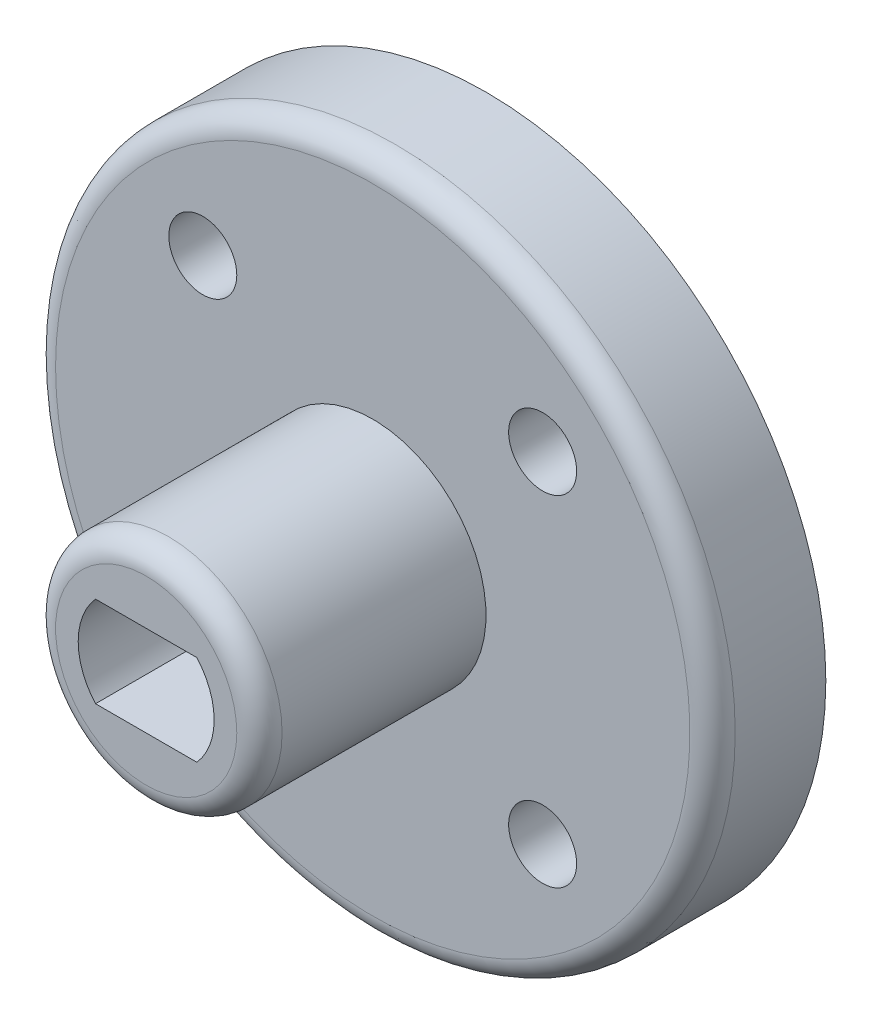
SolidWorks part; units mm, degrees
ref_plane "Alzado" through (0, 0, 0) normal (0, 0, 1) x (1, 0, 0)
ref_plane "Planta" through (0, 0, 0) normal (0, 1, 0) x (1, 0, 0)
ref_plane "Vista lateral" through (0, 0, 0) normal (1, 0, 0) x (0, 0, -1)
sketch "Croquis1" plane through (0, 0, 0) normal (0, 0, 1) x (1, 0, 0)
  line L0 (-7.3928, 0) -> (5.9139, 0) construction
  line L1 (-2.2361, -2) -> (2.2361, -2)
  line L2 (-2.2361, 2) -> (2.2361, 2)
  line L3 (-7.3928, 2) -> (5.9139, 2) construction
  line L4 (-7.3928, -2) -> (5.9139, -2) construction
  arc A0 (-2.2361, 2) -> (-2.2361, -2) centre (0, 0) ccw
  arc A1 (2.2361, -2) -> (2.2361, 2) centre (0, 0) ccw
  circle A2 centre (0, 0) radius 5
  dimension "D1" = 6
  dimension "D4" = 10
  dimension "D2" = 2
  dimension "D3" = 2
extrude "Saliente-Extruir1" add sketch "Croquis1" along normal mid plane 10
sketch "Croquis2" plane through (0, 0, -5) normal (0, 0, -1) x (-1, 0, 0)
  circle A0 centre (0, 0) radius 15
  dimension "D1" = 30
extrude "Saliente-Extruir2" add sketch "Croquis2" along normal blind 5
sketch "Croquis3" plane through (0, 0, -5) normal (0, 0, 1) x (1, 0, 0)
  line L1 (-7.5, -7.5) -> (7.5, -7.5) construction
  line L2 (-7.5, -7.5) -> (-7.5, 7.5) construction
  line L3 (-7.5, 7.5) -> (7.5, 7.5) construction
  line L4 (7.5, -7.5) -> (7.5, 7.5) construction
  line L5 (-7.5, -7.5) -> (7.5, 7.5) construction
  line L6 (-7.5, 7.5) -> (7.5, -7.5) construction
  circle A0 centre (-7.5, 7.5) radius 1.5
  circle A1 centre (7.5, 7.5) radius 1.5
  circle A2 centre (-7.5, -7.5) radius 1.5
  circle A3 centre (7.5, -7.5) radius 1.5
  point P0 (0, 0)
  dimension "D3" = 3
  dimension "D1" = 15
  dimension "D2" = 15
extrude "Cortar-Extruir1" cut sketch "Croquis3" against normal blind 5 contours A3 | A2 | A1 | A0
fillet "Redondeo1" radius 1 1 edges at (-15, 0, -5)
fillet "Redondeo2" radius 1 1 edges at (5, 0, 5)
